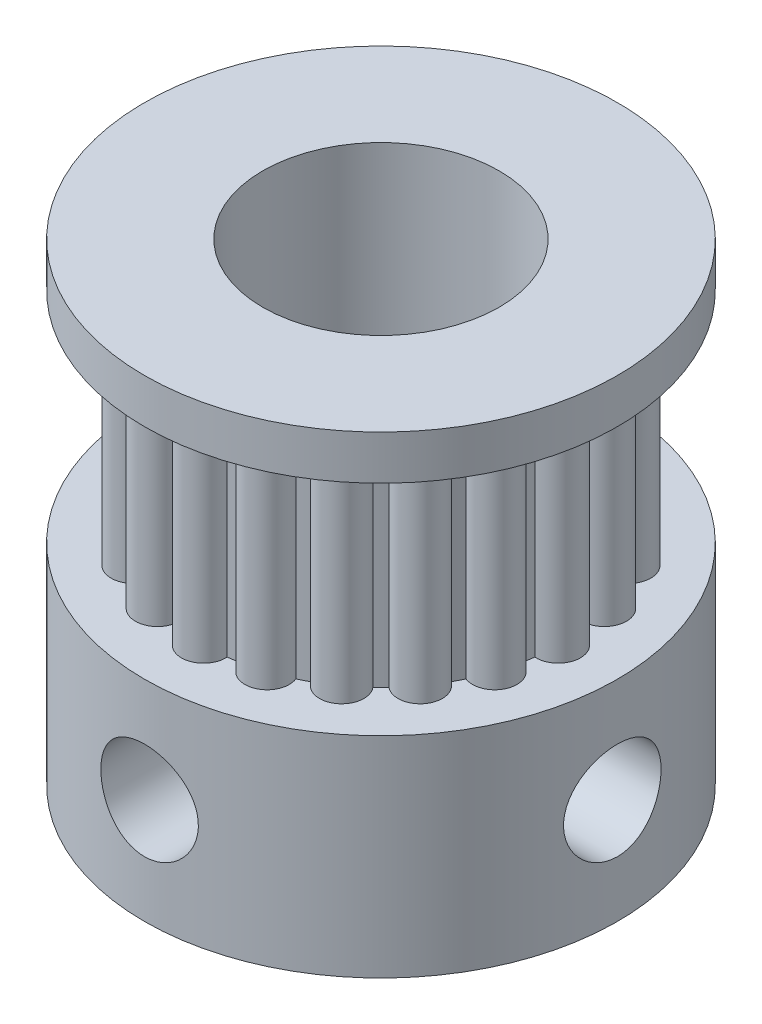
SolidWorks part; units mm, degrees
material "6061-T6 (SS)"
ref_plane "前视基准面" through (0, 0, 0) normal (0, 0, 1) x (1, 0, 0)
ref_plane "上视基准面" through (0, 0, 0) normal (0, 1, 0) x (1, 0, 0)
ref_plane "右视基准面" through (0, 0, 0) normal (1, 0, 0) x (0, 0, -1)
sketch "草图1" plane through (0, 0, 0) normal (0, 0, 1) x (1, 0, 0)
  line L0 (0, 30.8774) -> (0, 0) construction
  line L1 (0, 0) -> (-33.8317, 0) construction
  line L2 (-8, 16) -> (-4, 16)
  line L3 (-4, 16) -> (-4, 0)
  line L4 (-4, 0) -> (-8, 0)
  line L5 (-8, 0) -> (-8, 7.1)
  line L6 (-8, 7.1) -> (-6, 7.1)
  line L7 (-6, 7.1) -> (-6, 14.5)
  line L8 (-6, 14.5) -> (-8, 14.5)
  line L9 (-8, 14.5) -> (-8, 16)
  dimension "D1" = 4
  dimension "D2" = 16
  dimension "D3" = 7.4
  dimension "D4" = 6
  dimension "D5" = 8
  dimension "D6" = 1.5
revolve "旋转1" add sketch "草图1" angle 360 about L0
sketch "草图4" plane through (0, 0, 0) normal (0, 0, 1) x (1, 0, 0)
  line L0 (-8, 0) -> (8, 0) construction
  circle A0 centre (0, 3.55) radius 2
  dimension "D1" = 3.55
  dimension "D2" = 4
hole_wizard "M4 螺纹孔1" positions "3D草图5" profile "草图8" tap size "M4" standard "GB"
sketch3d "3D草图5"
  point P0 (0, 3.55, 8)
  point P2 (8, 3.55, 0)
  dimension "D1" = 0
  dimension "D2" = 3.55
  dimension "D3" = 0
  dimension "D4" = 3.55
sketch "草图8" plane through (0, 3.55, 8) normal (1, 0, 0) x (0, -1, 0)
  line L0 (0, 0) -> (0, 11.0914)
  line L1 (0, 11.0914) -> (1.65, 10.1)
  line L2 (1.65, 10.1) -> (1.65, 0)
  line L5 (1.65, 0) -> (0, 0)
  line L10 (0, 11.0914) -> (-1.65, 10.1) construction
  line L11 (0, -6.35) -> (0, 107.95) construction
  dimension "螺纹孔钻头直径" = 3.3
  dimension "螺纹孔钻头深度" = 10.1
  dimension "导头角度" = 118
cosmetic thread "孔螺蚊线1" parameters "D1"=4.3562, "D2"=4
cosmetic thread "孔螺蚊线2" parameters "D1"=4.3562, "D2"=4
sketch "草图9" plane through (0, 7.1, 0) normal (0, 1, 0) x (1, 0, 0)
  circle A0 centre (6, 0) radius 0.75
  circle A1 centre (0, 0) radius 6 construction
  dimension "D1" = 1.5
extrude "凸台-拉伸1" add sketch "草图9" along normal blind 8
pattern_circular "阵列(圆周)1" count 20 over 360 about axis through (0, 0, 0) along (0, 1, 0) of "凸台-拉伸1"
